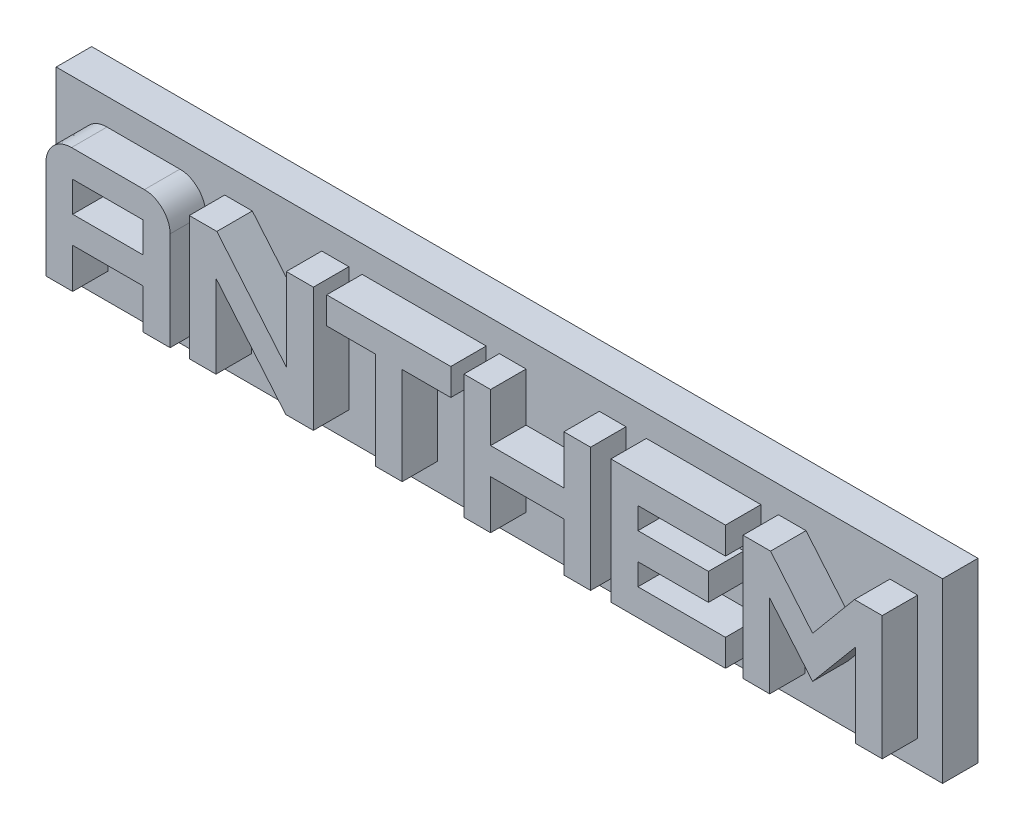
SolidWorks part; units mm, degrees
ref_plane "Front Plane" through (0, 0, 0) normal (0, 0, 1) x (1, 0, 0)
ref_plane "Top Plane" through (0, 0, 0) normal (0, 1, 0) x (1, 0, 0)
ref_plane "Right Plane" through (0, 0, 0) normal (1, 0, 0) x (0, 0, -1)
sketch "Sketch1" plane through (0, 0, 0) normal (0, 0, 1) x (1, 0, 0)
  text T0 "ANTHEM" font "Orbitron Black" height 3.5
extrude "Boss-Extrude1" add sketch "Sketch1" along normal blind 1
sketch "Sketch2" plane through (0, 0, 0) normal (0, 0, -1) x (-1, 0, 0)
  line L7 (-24.5689, 4.25) -> (0.4311, 4.25)
  line L8 (-24.5689, 4.25) -> (-24.5689, -0.75)
  line L9 (-24.5689, -0.75) -> (0.4311, -0.75)
  line L10 (0.4311, 4.25) -> (0.4311, -0.75)
  line L11 (-24.5689, 4.25) -> (0.4311, -0.75) construction
  line L12 (-24.5689, -0.75) -> (0.4311, 4.25) construction
  line L13 (-12.0689, 0) -> (-12.0689, 3.5) construction
  point P0 (-12.0689, 1.75)
  point P5 (-12.0689, 1.75)
  dimension "D3" = 5
  dimension "D4" = 25
extrude "Boss-Extrude2" add sketch "Sketch2" along normal blind 1
